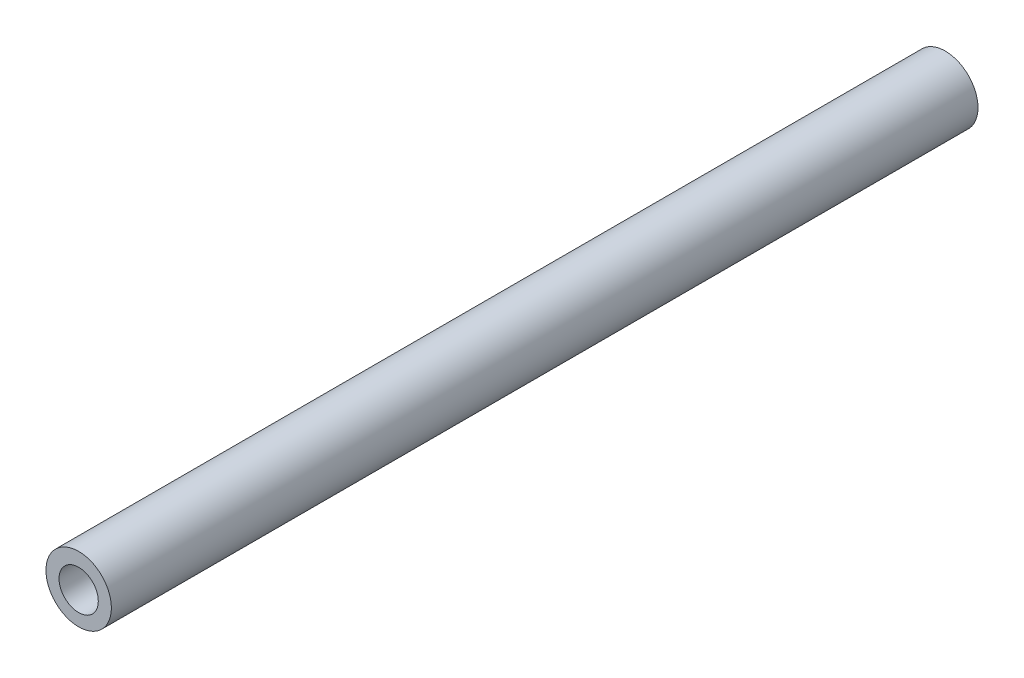
SolidWorks part; units mm, degrees
ref_plane "Front Plane" through (0, 0, 0) normal (0, 0, 1) x (1, 0, 0)
ref_plane "Top Plane" through (0, 0, 0) normal (0, 1, 0) x (1, 0, 0)
ref_plane "Right Plane" through (0, 0, 0) normal (1, 0, 0) x (0, 0, -1)
sketch "Sketch1" plane through (0, 0, 0) normal (0, 0, 1) x (1, 0, 0)
  circle A0 centre (0.0523, 0.0784) radius 3
  circle A1 centre (0.0523, 0.183) radius 5
  dimension "D1" = 6
  dimension "D2" = 10
extrude "Boss-Extrude1" add sketch "Sketch1" along normal blind 132.4
